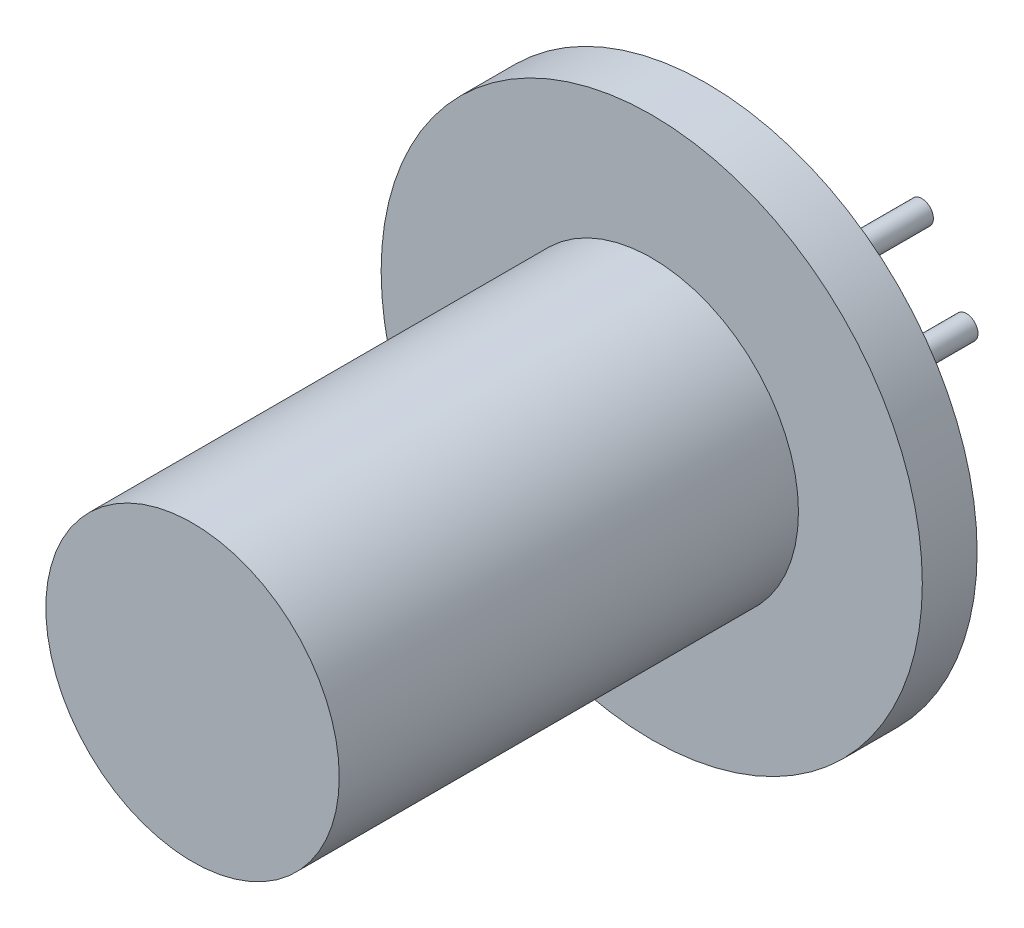
SolidWorks part; units mm, degrees
ref_plane "Front Plane" through (0, 0, 0) normal (0, 0, 1) x (1, 0, 0)
ref_plane "Top Plane" through (0, 0, 0) normal (0, 1, 0) x (1, 0, 0)
ref_plane "Right Plane" through (0, 0, 0) normal (1, 0, 0) x (0, 0, -1)
sketch "Sketch3" plane through (0, 0, 0) normal (0, 1, 0) x (1, 0, 0)
  line L0 (0, 0) -> (0, 3.1852)
  line L1 (0, 3.1852) -> (3.1623, 3.1852)
  line L2 (3.1623, 3.1852) -> (3.1623, 3.8354)
  line L3 (3.1623, 3.8354) -> (4.2799, 3.8354)
  line L4 (4.2799, 3.8354) -> (4.2799, 1.6129)
  line L5 (4.2799, 1.6129) -> (7.9629, 1.6129)
  line L6 (7.9629, 1.6129) -> (7.9629, 0)
  line L7 (7.9629, 0) -> (4.318, 0)
  line L8 (4.318, 0) -> (4.318, -13.5128)
  line L9 (4.318, -13.5128) -> (0, -13.5128)
  line L10 (0, -13.5128) -> (0, 0)
  point P12 (0, 1.5926)
  dimension "D1" = 1.1176
  dimension "D2" = 2.2225
  dimension "D3" = 3.683
  dimension "D4" = 1.6129
  dimension "D5" = 7.9629
  dimension "D6" = 4.318
  dimension "D7" = 13.5128
revolve "Revolve1" add sketch "Sketch3" angle 360 about L10
sketch "Sketch4" plane through (0, 0, -3.1852) normal (0, 0, -1) x (-1, 0, 0)
  circle A0 centre (0, 1.5162) radius 0.3409
  circle A1 centre (1.3131, -0.7581) radius 0.3409
  circle A2 centre (-1.3131, -0.7581) radius 0.3409
  point P8 (0, 0)
  dimension "D1" = 3
extrude "Boss-Extrude1" add sketch "Sketch4" along normal blind 4.7625
